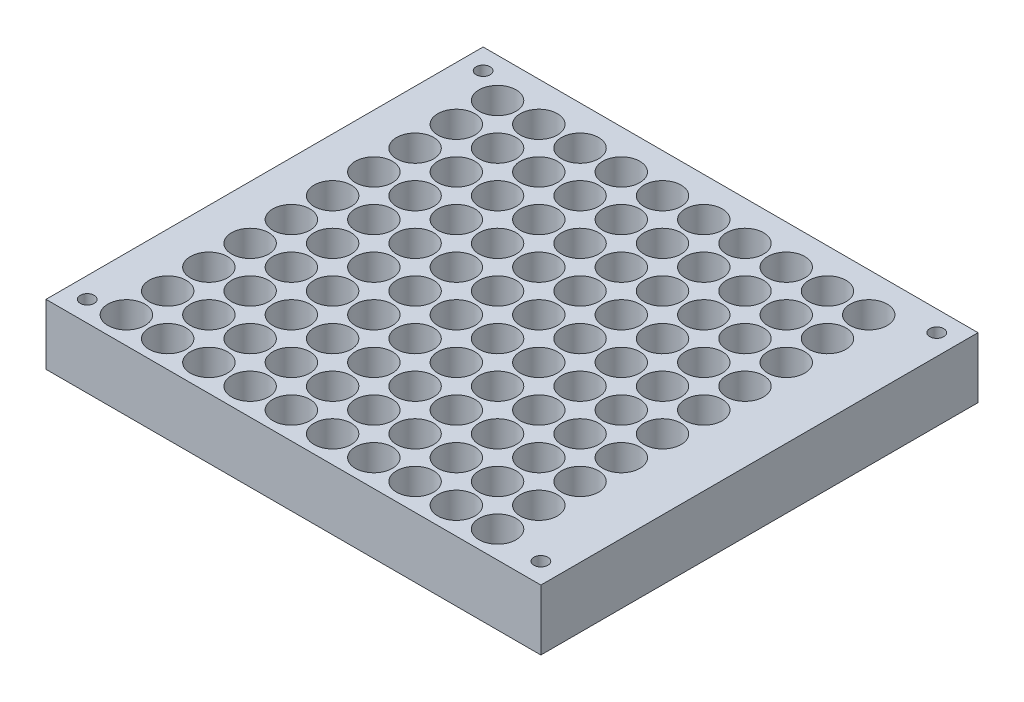
SolidWorks part; units mm, degrees
ref_plane "Front Plane" through (0, 0, 0) normal (0, 0, 1) x (1, 0, 0)
ref_plane "Top Plane" through (0, 0, 0) normal (0, 1, 0) x (1, 0, 0)
ref_plane "Right Plane" through (0, 0, 0) normal (1, 0, 0) x (0, 0, -1)
sketch "Sketch1" plane through (0, 0, 0) normal (0, 1, 0) x (1, 0, 0)
  line L0 (115, 101) -> (5, 101) construction
  line L1 (0, 0) -> (120, 0)
  line L2 (0, 0) -> (0, 106)
  line L3 (0, 106) -> (120, 106)
  line L4 (120, 0) -> (120, 106)
  line L6 (115, 101) -> (115, 5) construction
  circle A17 centre (13, 36.5) radius 4.5
  circle A18 centre (23, 36.5) radius 4.5
  circle A19 centre (13, 6.5) radius 4.5
  circle A28 centre (5, 5) radius 1.7
  circle A29 centre (5, 101) radius 1.7
  circle A30 centre (115, 101) radius 1.7
  circle A31 centre (115, 5) radius 1.7
  circle A32 centre (23, 6.5) radius 4.5
  circle A33 centre (33, 6.5) radius 4.5
  circle A34 centre (23, 16.5) radius 4.5
  circle A35 centre (33, 16.5) radius 4.5
  circle A36 centre (23, 26.5) radius 4.5
  circle A37 centre (33, 26.5) radius 4.5
  circle A38 centre (13, 16.5) radius 4.5
  circle A39 centre (13, 26.5) radius 4.5
  circle A40 centre (33, 36.5) radius 4.5
  circle A41 centre (13, 46.5) radius 4.5
  circle A42 centre (23, 46.5) radius 4.5
  circle A43 centre (33, 46.5) radius 4.5
  circle A44 centre (13, 56.5) radius 4.5
  circle A45 centre (23, 56.5) radius 4.5
  circle A46 centre (33, 56.5) radius 4.5
  circle A47 centre (13, 66.5) radius 4.5
  circle A48 centre (23, 66.5) radius 4.5
  circle A49 centre (33, 66.5) radius 4.5
  circle A50 centre (13, 76.5) radius 4.5
  circle A51 centre (23, 76.5) radius 4.5
  circle A52 centre (33, 76.5) radius 4.5
  circle A53 centre (13, 86.5) radius 4.5
  circle A54 centre (23, 86.5) radius 4.5
  circle A55 centre (33, 86.5) radius 4.5
  circle A56 centre (13, 96.5) radius 4.5
  circle A57 centre (23, 96.5) radius 4.5
  circle A58 centre (33, 96.5) radius 4.5
  circle A59 centre (43, 6.5) radius 4.5
  circle A60 centre (53, 6.5) radius 4.5
  circle A61 centre (63, 6.5) radius 4.5
  circle A62 centre (73, 6.5) radius 4.5
  circle A63 centre (83, 6.5) radius 4.5
  circle A64 centre (93, 6.5) radius 4.5
  circle A65 centre (103, 6.5) radius 4.5
  circle A66 centre (43, 16.5) radius 4.5
  circle A67 centre (53, 16.5) radius 4.5
  circle A68 centre (63, 16.5) radius 4.5
  circle A69 centre (73, 16.5) radius 4.5
  circle A70 centre (83, 16.5) radius 4.5
  circle A71 centre (93, 16.5) radius 4.5
  circle A72 centre (103, 16.5) radius 4.5
  circle A73 centre (43, 26.5) radius 4.5
  circle A74 centre (53, 26.5) radius 4.5
  circle A75 centre (63, 26.5) radius 4.5
  circle A76 centre (73, 26.5) radius 4.5
  circle A77 centre (83, 26.5) radius 4.5
  circle A78 centre (93, 26.5) radius 4.5
  circle A79 centre (103, 26.5) radius 4.5
  circle A80 centre (43, 36.5) radius 4.5
  circle A81 centre (53, 36.5) radius 4.5
  circle A82 centre (63, 36.5) radius 4.5
  circle A83 centre (73, 36.5) radius 4.5
  circle A84 centre (83, 36.5) radius 4.5
  circle A85 centre (93, 36.5) radius 4.5
  circle A86 centre (103, 36.5) radius 4.5
  circle A87 centre (43, 46.5) radius 4.5
  circle A88 centre (53, 46.5) radius 4.5
  circle A89 centre (63, 46.5) radius 4.5
  circle A90 centre (73, 46.5) radius 4.5
  circle A91 centre (83, 46.5) radius 4.5
  circle A92 centre (93, 46.5) radius 4.5
  circle A93 centre (103, 46.5) radius 4.5
  circle A94 centre (43, 56.5) radius 4.5
  circle A95 centre (53, 56.5) radius 4.5
  circle A96 centre (63, 56.5) radius 4.5
  circle A97 centre (73, 56.5) radius 4.5
  circle A98 centre (83, 56.5) radius 4.5
  circle A99 centre (93, 56.5) radius 4.5
  circle A100 centre (103, 56.5) radius 4.5
  circle A101 centre (43, 66.5) radius 4.5
  circle A102 centre (53, 66.5) radius 4.5
  circle A103 centre (63, 66.5) radius 4.5
  circle A104 centre (73, 66.5) radius 4.5
  circle A105 centre (83, 66.5) radius 4.5
  circle A106 centre (93, 66.5) radius 4.5
  circle A107 centre (103, 66.5) radius 4.5
  circle A108 centre (43, 76.5) radius 4.5
  circle A109 centre (53, 76.5) radius 4.5
  circle A110 centre (63, 76.5) radius 4.5
  circle A111 centre (73, 76.5) radius 4.5
  circle A112 centre (83, 76.5) radius 4.5
  circle A113 centre (93, 76.5) radius 4.5
  circle A114 centre (103, 76.5) radius 4.5
  circle A115 centre (43, 86.5) radius 4.5
  circle A116 centre (53, 86.5) radius 4.5
  circle A117 centre (63, 86.5) radius 4.5
  circle A118 centre (73, 86.5) radius 4.5
  circle A119 centre (83, 86.5) radius 4.5
  circle A120 centre (93, 86.5) radius 4.5
  circle A121 centre (103, 86.5) radius 4.5
  circle A122 centre (43, 96.5) radius 4.5
  circle A123 centre (53, 96.5) radius 4.5
  circle A124 centre (63, 96.5) radius 4.5
  circle A125 centre (73, 96.5) radius 4.5
  circle A126 centre (83, 96.5) radius 4.5
  circle A127 centre (93, 96.5) radius 4.5
  circle A128 centre (103, 96.5) radius 4.5
  point P7 (115, 53)
  point P9 (60, 101)
  point P10 (60, 106)
  point P20 (120, 53)
  dimension "D5" = 110
  dimension "D6" = 96
  dimension "D3" = 9
  dimension "D8" = 3.4
  dimension "D1" = 120
  dimension "D2" = 106
  dimension "D4" = 8
  dimension "D7" = 1.5
  dimension "D9" = 10
  dimension "D10" = 10
extrude "Boss-Extrude1" add sketch "Sketch1" along normal blind 14.7
equation "\"o\"= 10mm"
equation "\"P\"= 10"
